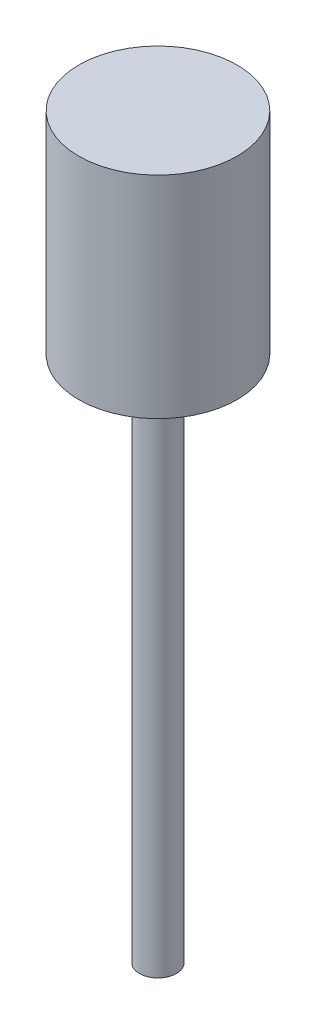
SolidWorks part; units mm, degrees
material "AISI 316 Stainless Steel Sheet (SS)"
ref_plane "Front Plane" through (0, 0, 0) normal (0, 0, 1) x (1, 0, 0)
ref_plane "Top Plane" through (0, 0, 0) normal (0, 1, 0) x (1, 0, 0)
ref_plane "Right Plane" through (0, 0, 0) normal (1, 0, 0) x (0, 0, -1)
sketch "Sketch1" plane through (0, 0, 0) normal (0, 1, 0) x (1, 0, 0)
  circle A0 centre (0, 0) radius 4.445
  dimension "D1" = 8.89
extrude "Boss-Extrude1" add sketch "Sketch1" along normal blind 127
sketch "Sketch2" plane through (0, 127, 0) normal (0, 1, 0) x (1, 0, 0)
  circle A0 centre (0, 0) radius 19.05
  dimension "D1" = 38.1
extrude "Boss-Extrude2" add sketch "Sketch2" along normal blind 50.8
